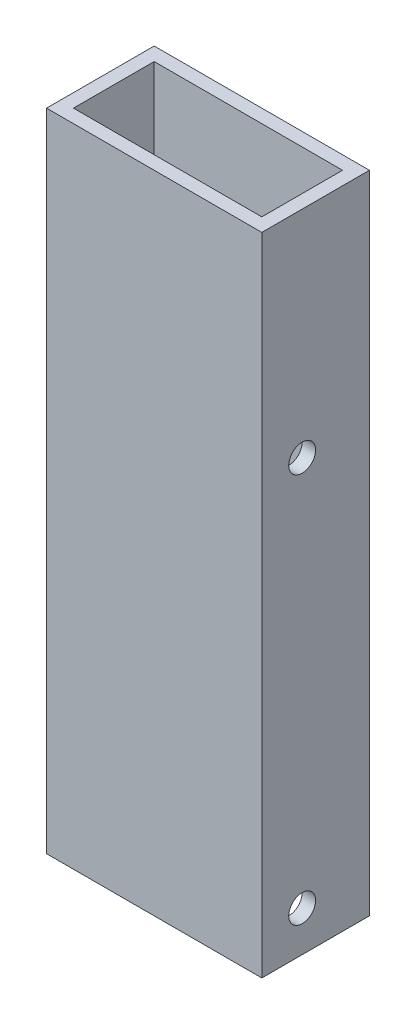
SolidWorks part; units mm, degrees
material "6061-T6 (SS)"
ref_plane "Front Plane" through (0, 0, 0) normal (0, 0, 1) x (1, 0, 0)
ref_plane "Top Plane" through (0, 0, 0) normal (0, 1, 0) x (1, 0, 0)
ref_plane "Right Plane" through (0, 0, 0) normal (1, 0, 0) x (0, 0, -1)
sketch "Sketch1" plane through (0, 0, 0) normal (0, 1, 0) x (1, 0, 0)
  line L1 (-25.4, 12.7) -> (25.4, 12.7)
  line L2 (-25.4, 12.7) -> (-25.4, -12.7)
  line L3 (-25.4, -12.7) -> (25.4, -12.7)
  line L4 (25.4, 12.7) -> (25.4, -12.7)
  line L5 (-25.4, 12.7) -> (25.4, -12.7) construction
  line L6 (-25.4, -12.7) -> (25.4, 12.7) construction
  line L7 (-22.225, 9.525) -> (22.225, 9.525)
  line L8 (-22.225, 9.525) -> (-22.225, -9.525)
  line L9 (-22.225, -9.525) -> (22.225, -9.525)
  line L10 (22.225, 9.525) -> (22.225, -9.525)
  line L11 (-22.225, 9.525) -> (22.225, -9.525) construction
  line L12 (-22.225, -9.525) -> (22.225, 9.525) construction
  point P0 (0, 0)
  point P6 (0, 0)
  dimension "D1" = 50.8
  dimension "D2" = 25.4
  dimension "D3" = 44.45
  dimension "D4" = 19.05
extrude "Boss-Extrude1" add sketch "Sketch1" along normal mid plane 152.4
sketch "Sketch2" plane through (-25.4, 0, 0) normal (-1, 0, 0) x (0, 0, 1)
  line L3 (-12.7, -76.2) -> (12.7, -76.2) construction
  line L6 (12.7, 76.2) -> (12.7, -76.2) construction
  circle A0 centre (3.175, -66.675) radius 3.175
  circle A1 centre (3.175, 25.4) radius 3.175
  dimension "D1" = 6.35
  dimension "D2" = 6.35
  dimension "D4" = 6.35
  dimension "D3" = 85.725
extrude "Cut-Extrude1" cut sketch "Sketch2" against normal through all
